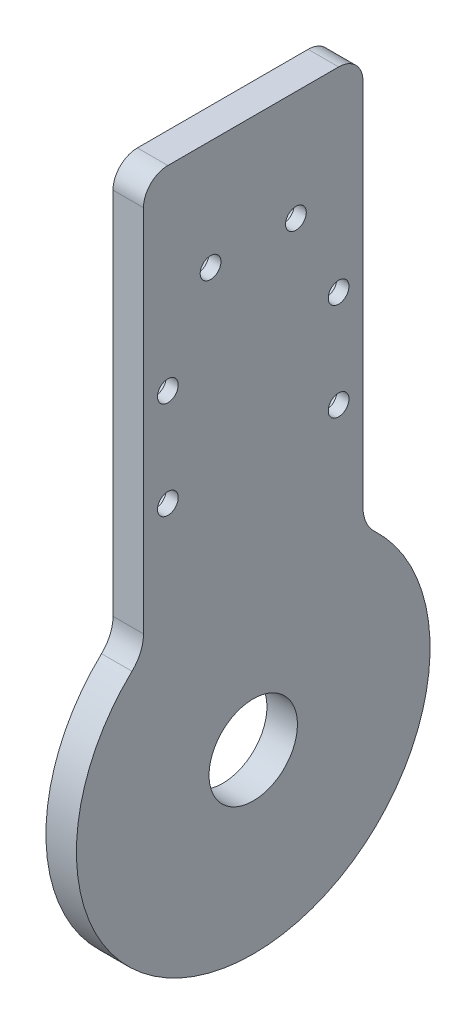
SolidWorks part; units mm, degrees
ref_plane "Front Plane" through (0, 0, 0) normal (0, 0, 1) x (1, 0, 0)
ref_plane "Top Plane" through (0, 0, 0) normal (0, 1, 0) x (1, 0, 0)
ref_plane "Right Plane" through (0, 0, 0) normal (1, 0, 0) x (0, 0, -1)
sketch "Sketch1" plane through (0, 0, 0) normal (1, 0, 0) x (0, 0, -1)
  line L0 (-32, 227.9755) -> (-32, 288.5)
  line L1 (-28, 292.5) -> (0, 292.5)
  line L2 (4, 288.5) -> (4, 227.9755)
  arc A0 (5.8857, 223.6083) -> (-33.8857, 223.6083) centre (-14, 202.5) cw
  arc A1 (-33.8857, 223.6083) -> (-32, 227.9755) centre (-38, 227.9755) ccw
  arc A2 (-32, 288.5) -> (-28, 292.5) centre (-28, 288.5) cw
  arc A3 (0, 292.5) -> (4, 288.5) centre (0, 288.5) cw
  arc A4 (4, 227.9755) -> (5.8857, 223.6083) centre (10, 227.9755) ccw
  circle A5 centre (-14, 202.5) radius 7.25
extrude "Plate I" add sketch "Sketch1" along normal blind 5 from offset 33.55
sketch "Sketch2" plane through (0, 0, 0) normal (1, 0, 0) x (0, 0, -1)
  circle A0 centre (0, 244.5) radius 1.7
  circle A1 centre (-28, 244.5) radius 1.7
  circle A2 centre (0, 260.5) radius 1.7
  circle A3 centre (-28, 260.5) radius 1.7
  circle A4 centre (-7, 274.5) radius 1.7
  circle A5 centre (-21, 274.5) radius 1.7
extrude "Bolt holes" cut sketch "Sketch2" along normal blind 5.4 from offset 33.75
sketch "Sketch3" plane through (0, 0, 0) normal (1, 0, 0) x (0, 0, -1)
  circle A0 centre (0, 244.5) radius 3.2
  circle A1 centre (-28, 244.5) radius 3.2
  circle A2 centre (0, 260.5) radius 3.2
  circle A3 centre (-28, 260.5) radius 3.2
  circle A4 centre (-7, 274.5) radius 3.2
  circle A5 centre (-21, 274.5) radius 3.2
extrude "Counterbores" cut sketch "Sketch3" along normal blind 3.2 from offset 33.75
